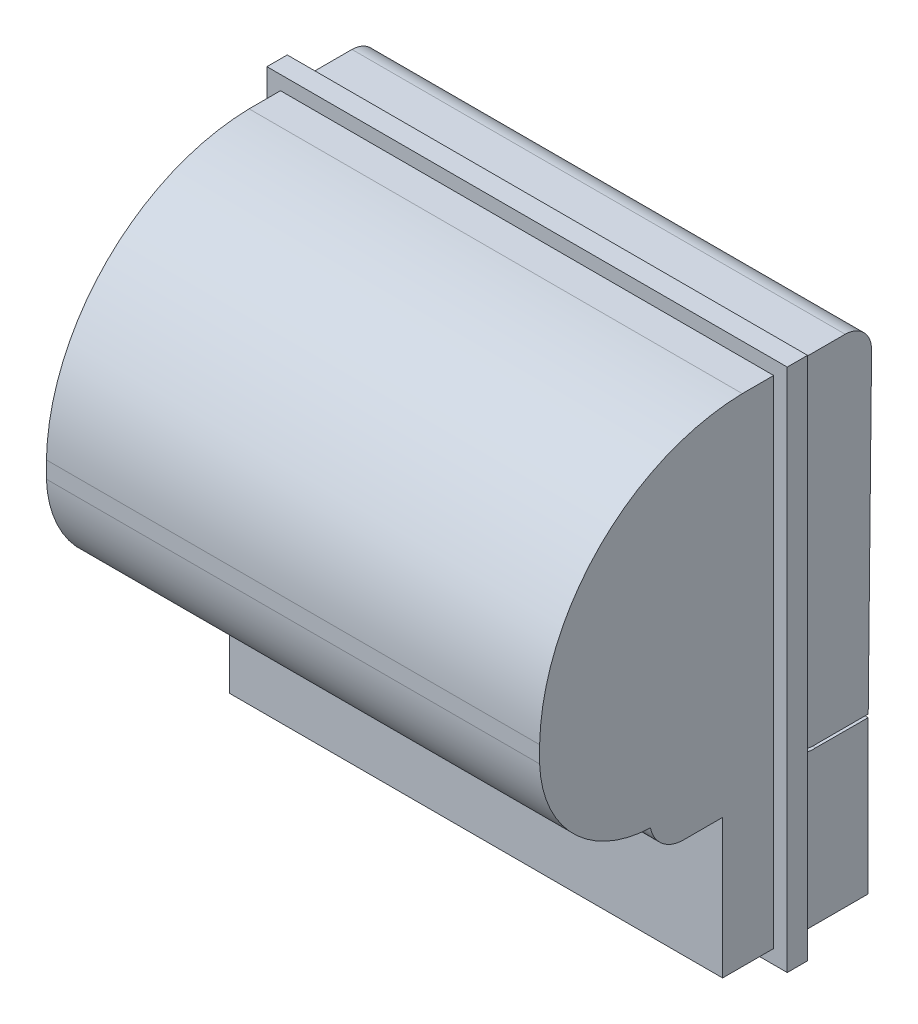
SolidWorks part; units mm, degrees
ref_plane "Front Plane" through (0, 0, 0) normal (0, 0, 1) x (1, 0, 0)
ref_plane "Top Plane" through (0, 0, 0) normal (0, 1, 0) x (1, 0, 0)
ref_plane "Right Plane" through (0, 0, 0) normal (1, 0, 0) x (0, 0, -1)
sketch "Sketch1" plane through (0, 0, 0) normal (0, 0, 1) x (1, 0, 0)
  line L0 (0, 0) -> (76.8, 0)
  line L1 (76.8, 0) -> (76.8, 77.4)
  line L2 (76.8, 77.4) -> (0, 77.4)
  line L3 (0, 77.4) -> (0, 0)
  line L4 (38.4, 77.4) -> (38.4, 0) construction
  line L5 (0, 38.7) -> (76.8, 38.7) construction
  line L6 (2, 75.325) -> (2, 2.075)
  line L7 (2, 75.325) -> (74.8, 75.325)
  line L8 (74.8, 75.325) -> (74.8, 2.075)
  line L9 (74.8, 2.075) -> (2, 2.075)
  dimension "D1" = 77.4
  dimension "D2" = 76.8
  dimension "D3" = 73.25
  dimension "D4" = 72.8
extrude "Boss-Extrude1" add sketch "Sketch1" along normal blind 3
ref_plane "Plane1" through (38.4, 0, 0) normal (-1, 0, 0) x (0, 0, 1)
sketch "Sketch3" plane through (38.4, 0, 0) normal (-1, 0, 0) x (0, 0, 1)
  line L0 (3, 75.325) -> (37.55, 75.325)
  line L1 (37.55, 75.325) -> (37.55, 2.075)
  line L2 (37.55, 2.075) -> (3, 2.075)
  line L3 (3, 75.325) -> (-11.45, 75.325)
  line L4 (-11.45, 75.325) -> (-11.45, 2.075)
  line L5 (-11.45, 2.075) -> (3, 2.075)
  dimension "D1" = 49
  dimension "D2" = 34.55
extrude "Boss-Extrude2" add sketch "Sketch3" along normal up to surface and the other way up to surface up to face at (2, 38.7, 1.5) other way up to face at (74.8, 38.7, 1.5)
sketch "Sketch4" plane through (38.4, 0, 0) normal (-1, 0, 0) x (0, 0, 1)
  line L0 (3, 75.325) -> (37.55, 75.325) construction
  line L1 (37.55, 75.325) -> (37.55, 2.075) construction
  line L2 (-11.45, 75.325) -> (0, 75.325) construction
  line L3 (-11.45, 2.075) -> (-11.45, 75.325) construction
  line L4 (-11.45, 71.4276) -> (-10.95, 25.0693)
  line L6 (16.2829, 22.6083) -> (10.54, 22.6083)
  line L7 (10.54, 22.6083) -> (10.54, 2.075)
  line L8 (37.55, 2.075) -> (3, 2.075) construction
  line L10 (-10.95, 25.0693) -> (-3.1599, 25.0693)
  line L11 (0, 77.4) -> (0, 0) construction
  line L12 (0, 27.6294) -> (0, 27.1294)
  line L13 (-3.1599, 24.6345) -> (-10.95, 24.6151)
  line L14 (-10.95, 24.6151) -> (-10.95, 2.075)
  line L15 (0, 2.075) -> (-11.45, 2.075) construction
  line L18 (7.634, 75.325) -> (37.55, 75.325)
  line L19 (37.55, 75.325) -> (37.55, 44.1661)
  line L20 (37.55, 44.1661) -> (37.55, 2.075)
  line L21 (37.55, 2.075) -> (10.54, 2.075)
  line L22 (-10.95, 2.075) -> (-11.45, 2.075)
  line L23 (-11.45, 2.075) -> (-11.45, 71.4276)
  line L24 (-11.45, 71.4276) -> (-11.45, 75.325)
  line L25 (-11.45, 75.325) -> (-7.4498, 75.325)
  arc A0 (7.634, 75.325) -> (37.55, 44.1661) centre (7.0126, 44.7876) cw
  arc A1 (-7.4498, 75.325) -> (-11.45, 71.4276) centre (-7.5012, 71.3762) ccw
  arc A2 (37.55, 44.1661) -> (21.1955, 26.5915) centre (20.5854, 43.5561) cw
  arc A3 (21.1955, 26.5915) -> (16.2829, 22.6083) centre (16.2829, 27.6294) cw
  arc A4 (-3.1599, 25.0693) -> (0, 27.6294) centre (-2.86, 27.9293) ccw
  arc A5 (0, 27.1294) -> (-3.1599, 24.6345) centre (-2.8274, 27.4619) cw
  dimension "D1" = 0.5
extrude "Cut-Extrude1" cut sketch "Sketch4" against normal blind 36.5 and the other way blind 36.5 contours L18 A0 L19 | A2 A3 L6 L7 L21 L20 | A1 L25 L24 | A5 L12 A4 L10 L4 L23 L22 L14 L13
